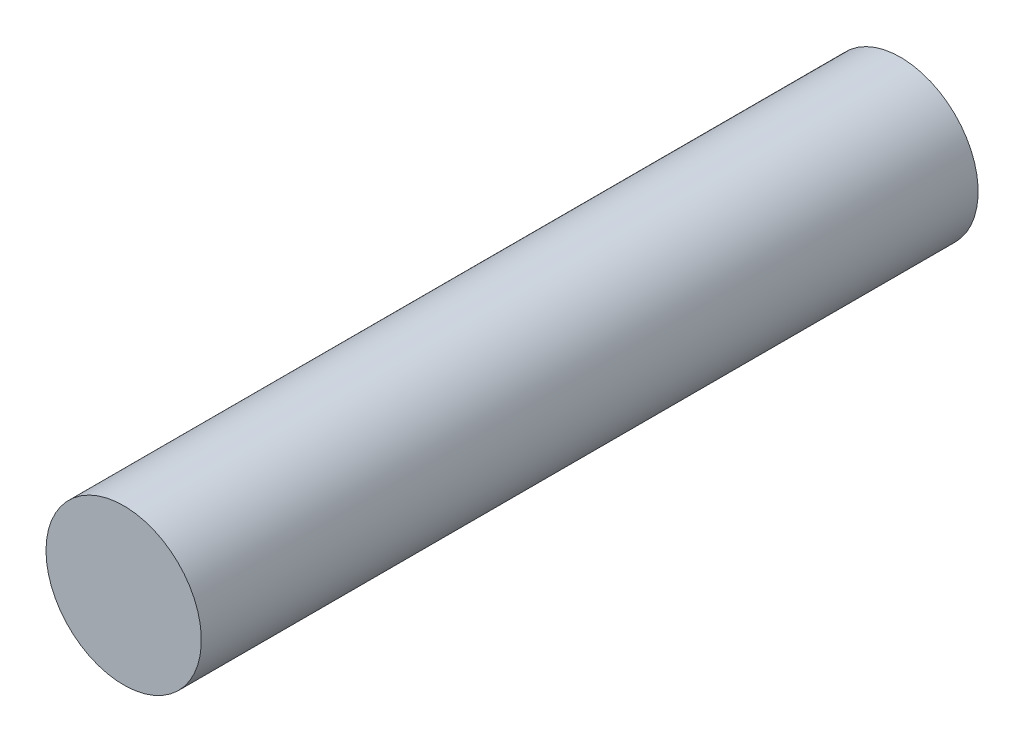
SolidWorks part; units mm, degrees
material "ABS"
ref_plane "Front Plane" through (0, 0, 0) normal (0, 0, 1) x (1, 0, 0)
ref_plane "Top Plane" through (0, 0, 0) normal (0, 1, 0) x (1, 0, 0)
ref_plane "Right Plane" through (0, 0, 0) normal (1, 0, 0) x (0, 0, -1)
sketch "Sketch2" plane through (0, 0, 0) normal (0, 0, 1) x (1, 0, 0)
  circle A0 centre (0, 0) radius 7.62
extrude "Boss-Extrude1" add sketch "Sketch2" along normal blind 76.2
